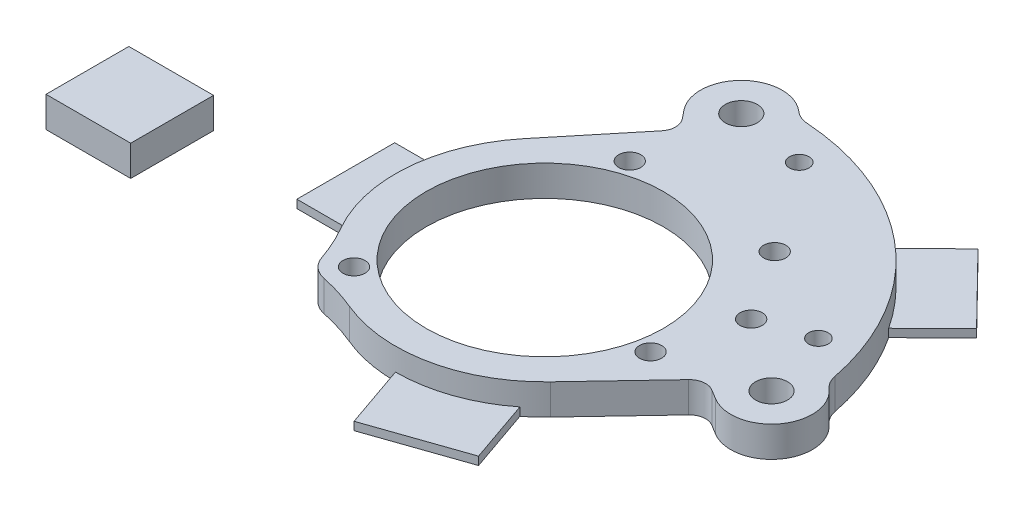
SolidWorks part; units mm, degrees
material "6061-T6 (SS)"
ref_plane "Front Plane" through (0, 0, 0) normal (0, 0, 1) x (1, 0, 0)
ref_plane "Top Plane" through (0, 0, 0) normal (0, 1, 0) x (1, 0, 0)
ref_plane "Right Plane" through (0, 0, 0) normal (1, 0, 0) x (0, 0, -1)
sketch "Sketch1" plane through (0, 0, 0) normal (0, 1, 0) x (1, 0, 0)
  line L0 (0, 0) -> (35.3283, 0) construction
  line L1 (0, 0) -> (-4.4339, 35.049) construction
  line L4 (35.3283, 0) -> (25.752, -15.7038) construction
  line L5 (25.752, -15.7038) -> (0, 0) construction
  line L6 (32.0223, -5.4215) -> (28.7694, -3.4378)
  line L7 (28.7694, -3.4378) -> (16.8994, -15.986)
  line L8 (-17.9806, 14.7595) -> (-7.0214, 28.1104)
  line L9 (-7.0214, 28.1104) -> (-9.3976, 31.0886)
  line L10 (-4.4339, 35.049) -> (-18.8117, 23.5775) construction
  line L11 (-18.8117, 23.5775) -> (0, 0) construction
  line L13 (0, 0) -> (16.7825, 19.0394) construction
  line L14 (0, 0) -> (24.0538, 8.0973) construction
  line L15 (24.0538, 8.0973) -> (14.5341, 16.4886) construction
  line L16 (14.5341, 16.4886) -> (0, 0) construction
  line L17 (39.5272, 4.7636) -> (-0.235, 39.8126) construction
  circle A0 centre (0, 0) radius 18.5 construction
  arc A1 (-17.9806, 14.7595) -> (16.8994, -15.986) centre (0, 0) ccw
  circle A2 centre (0, 0) radius 35.3283 construction
  arc A3 (32.0223, -5.4215) -> (39.5272, 4.7636) centre (35.3283, 0) ccw
  arc A4 (-0.235, 39.8126) -> (-9.3976, 31.0886) centre (-4.4339, 35.049) ccw
  circle A5 centre (16.7825, 19.0394) radius 0.127
  circle A6 centre (24.0538, 8.0973) radius 0.127
  arc A8 (39.5272, 4.7636) -> (38.3083, 6.8861) centre (42.0466, 7.6217) cw
  arc A9 (-0.235, 39.8126) -> (2.0237, 38.8696) centre (2.2843, 42.6707) ccw
  arc A10 (38.3083, 6.8861) -> (2.0237, 38.8696) centre (-0.6957, -0.7893) ccw
  circle A12 centre (0, 0) radius 18.4809
  dimension "D1" = 37
  dimension "D4" = 70.6567
  dimension "D5" = 12.7
  dimension "D8" = 0.254
  dimension "D11" = 39.752
  dimension "D12" = 3.81
  dimension "D2" = 4.7625
  dimension "D3" = 97.21
  dimension "D7" = 30.1625
  dimension "D6" = 25.3801
  dimension "D9" = 12.6901
  dimension "D10" = 21.9798
  dimension "D13" = 3.81
  dimension "D14" = 0.019
extrude "Boss-Extrude1" add sketch "Sketch1" along normal blind 4.7625
fillet "Fillet1" radius 2.54 2 edges at (-7.0214, 2.3813, -28.1104) (28.7694, 2.3813, 3.4378)
hole_wizard "#10 Clearance Hole1" positions "Sketch2" profile "Sketch3" hole size "#10" standard "ANSI Inch" end condition through all
sketch "Sketch2" plane through (0, 4.7625, 0) normal (0, 1, 0) x (1, 0, 0)
  point P0 (-4.4339, 35.049)
  point P3 (35.3283, 0)
sketch "Sketch3" plane through (-4.4339, 4.7625, -35.049) normal (1, 0, 0) x (0, 0, 1)
  line L0 (0, 0) -> (0, 4.7625)
  line L1 (0, 4.7625) -> (2.4892, 4.7625)
  line L2 (2.4892, 4.7625) -> (2.4892, 0)
  line L5 (2.4892, 0) -> (0, 0)
  line L11 (0, -6.35) -> (0, 107.95) construction
  dimension "Thru Hole Dia." = 4.9784
  dimension "Thru Hole Depth" = 4.7625
sketch "Sketch4" plane through (0, 4.7625, 0) normal (0, 1, 0) x (1, 0, 0)
  line L0 (0, 0) -> (6.6493, 32.9916) construction
  line L1 (0, 0) -> (31.8962, 10.7374) construction
  line L2 (0, 0) -> (16.7825, 19.0394) construction
  circle A0 centre (6.6493, 32.9916) radius 1.524
  circle A1 centre (31.8962, 10.7374) radius 1.524
  dimension "D1" = 3.048
  dimension "D2" = 33.655
  dimension "D3" = 30
  dimension "D4" = 30
extrude "Cut-Extrude1" cut sketch "Sketch4" against normal up to next
hole_wizard "#8-32 Tapped Hole1" positions "3DSketch3" profile "Sketch5" tap size "#8-32" standard "ANSI Inch"
sketch3d "3DSketch3"
  line L0 (0, 0, 0) -> (-13.9246, 4.7625, 15.7972) construction
  line L1 (-13.9246, 4.7625, 15.7972) -> (20.6431, 4.7625, 4.1605) construction
  line L2 (20.6431, 4.7625, 4.1605) -> (0, 0, 0) construction
  line L3 (0, 0, 0) -> (-6.7184, 4.7625, -19.9577) construction
  line L4 (-6.7184, 4.7625, -19.9577) -> (-13.9246, 4.7625, 15.7972) construction
  line L6 (-6.7184, 4.7625, -19.9577) -> (20.6431, 4.7625, 4.1605) construction
  line L8 (-4.4339, 4.7625, -35.049) -> (35.3283, 4.7625, 0) construction
  line L9 (-4.4339, 0, -35.049) -> (-4.4339, 4.7625, -35.049) construction
  line L10 (35.3283, 0, 0) -> (35.3283, 4.7625, 0) construction
  line L11 (16.7825, 4.7625, -19.0394) -> (16.7825, 0, -19.0394) construction
  line L12 (24.0538, 4.7625, -8.0973) -> (24.0538, 0, -8.0973) construction
  point P0 (-13.9246, 4.7625, 15.7972)
  point P2 (20.6431, 4.7625, 4.1605)
  point P4 (-6.7184, 4.7625, -19.9577)
  point P24 (16.7825, 4.7625, -19.0394)
  point P28 (24.0538, 4.7625, -8.0973)
  dimension "D1" = 21.59
sketch "Sketch5" plane through (-13.9246, 4.7625, 15.7972) normal (1, 0, 0) x (0, 0, 1)
  line L0 (0, 0) -> (0, 11.7566)
  line L1 (0, 11.7566) -> (1.7272, 10.7188)
  line L2 (1.7272, 10.7188) -> (1.7272, 0)
  line L5 (1.7272, 0) -> (0, 0)
  line L10 (0, 11.7566) -> (-1.7272, 10.7188) construction
  line L11 (0, -6.35) -> (0, 107.95) construction
  dimension "Tap Drill Dia." = 3.4544
  dimension "Tap Drill Depth" = 10.7188
  dimension "Drill Angle" = 118
cosmetic thread "Hole Thread1" parameters "D1"=4.7625, "D2"=4.1656
cosmetic thread "Hole Thread2" parameters "D1"=4.7625, "D2"=4.1656
cosmetic thread "Hole Thread3" parameters "D1"=4.7625, "D2"=4.1656
cosmetic thread "Hole Thread4" parameters "D1"=4.7625, "D2"=4.1656
cosmetic thread "Hole Thread5" parameters "D1"=4.7625, "D2"=4.1656
sketch "Sketch6" plane through (0, 4.7625, 0) normal (0, 1, 0) x (1, 0, 0)
  arc A3 (-17.8009, -14.9757) -> (-12.6231, -19.5397) centre (-13.9246, -15.7972) ccw
  arc A5 (-17.8009, -14.9757) -> (-12.6231, -19.5397) centre (0, 0) ccw
  arc A6 (-17.9806, 14.7595) -> (16.8994, -15.986) centre (0, 0) ccw construction
  dimension "D1" = 3.9624
extrude "Boss-Extrude2" add sketch "Sketch6" against normal up to surface (4.7625 mm away) up to face at (-13.9246, 0, 17.5244)
fillet "Fillet2" radius 31.75 2 edges at (-12.6231, 2.3813, 19.5397) (-17.8009, 2.3813, 14.9757)
sketch "Sketch7" plane through (0, 4.7625, 0) normal (0, 1, 0) x (1, 0, 0)
  line L1 (-48.008, -16.4992) -> (-61.2028, -16.4992)
  line L2 (-48.008, -16.4992) -> (-48.008, -3.5931)
  line L3 (-48.008, -3.5931) -> (-61.2028, -3.5931)
  line L4 (-61.2028, -16.4992) -> (-61.2028, -3.5931)
extrude "Boss-Extrude3" add sketch "Sketch7" against normal up to surface (4.7625 mm away) separate body up to face at (-13.9246, 0, 17.5244)
sketch "Sketch8" plane through (0, 0, 0) normal (0, -1, 0) x (1, 0, 0)
  line L0 (0, 23.2625) -> (14.3992, 18.2704)
  line L1 (0, 23.2625) -> (3.4193, 33.1252)
  line L2 (14.3992, 18.2704) -> (17.8185, 28.1331)
  line L3 (3.4193, 33.1252) -> (17.8185, 28.1331)
  line L4 (-21.9791, -7.62) -> (-21.9791, 7.62)
  line L5 (-21.9791, -7.62) -> (-30.9988, -7.62)
  line L6 (-21.9791, 7.62) -> (-30.9988, 7.62)
  line L7 (-30.9988, -7.62) -> (-30.9988, 7.62)
  line L8 (32.5075, -21.0688) -> (21.8429, -31.9557)
  line L9 (32.5075, -21.0688) -> (39.425, -27.845)
  line L10 (21.8429, -31.9557) -> (28.7605, -38.7319)
  line L11 (39.425, -27.845) -> (28.7605, -38.7319)
  arc A0 (16.8994, 15.986) -> (-8.9704, 21.4634) centre (0, 0) ccw construction
  arc A1 (-20.1678, 11.5932) -> (-17.9806, -14.7595) centre (0, 0) ccw construction
  arc A2 (2.0237, -38.8696) -> (38.3083, -6.8861) centre (-0.6957, 0.7893) ccw construction
  dimension "D1" = 15.24
extrude "Boss-Extrude4" add sketch "Sketch8" against normal blind 1.27
equation "\"D1@Sketch1\"=37mm"
